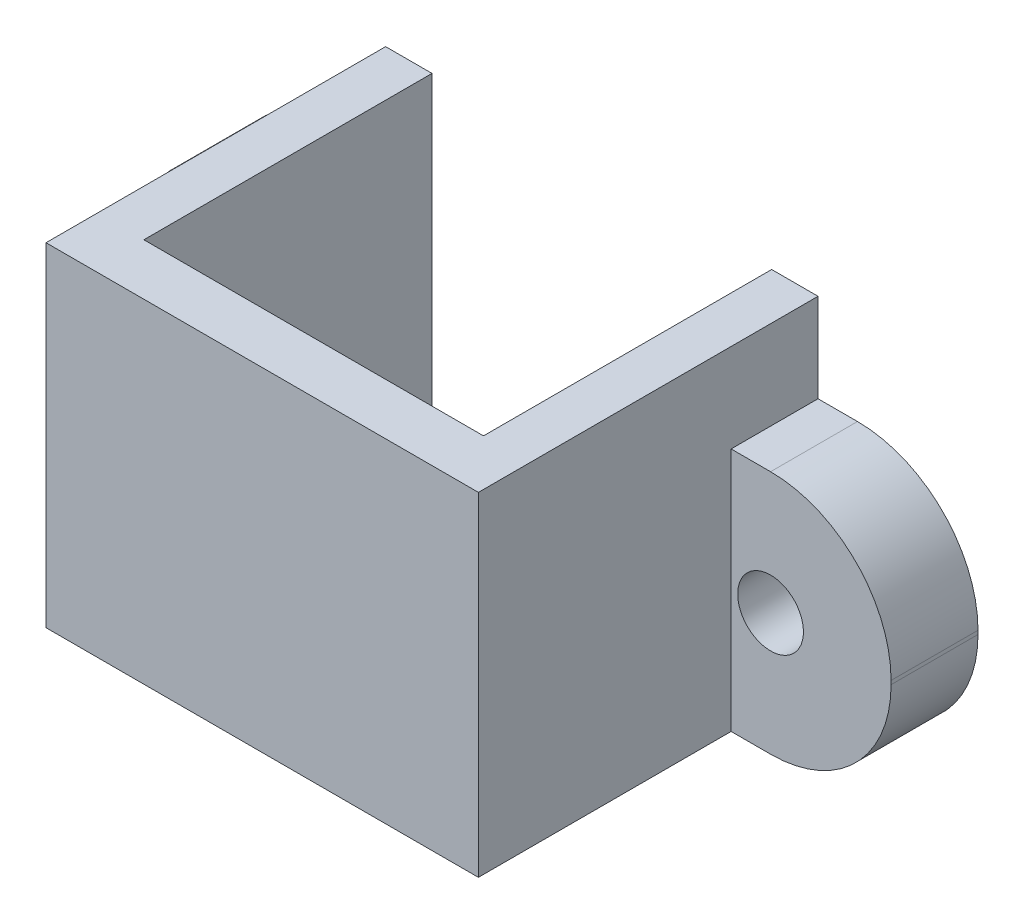
SolidWorks part; units mm, degrees
ref_plane "Front Plane" through (0, 0, 0) normal (0, 0, 1) x (1, 0, 0)
ref_plane "Top Plane" through (0, 0, 0) normal (0, 1, 0) x (1, 0, 0)
ref_plane "Right Plane" through (0, 0, 0) normal (1, 0, 0) x (0, 0, -1)
sketch "Sketch1" plane through (0, 0, 0) normal (0, 1, 0) x (1, 0, 0)
  line L0 (0, 0) -> (7.1755, 0)
  line L1 (7.1755, 0) -> (7.1755, -10.0203)
  line L2 (7.1755, -10.0203) -> (18.9865, -10.0203)
  line L3 (18.9865, -10.0203) -> (18.9865, 0)
  line L4 (18.9865, 0) -> (26.162, 0)
  line L5 (26.162, 0) -> (26.162, -3.0226)
  line L6 (0, -3.0226) -> (5.5626, -3.0226)
  line L7 (5.5626, -3.0226) -> (5.5626, -11.811)
  line L8 (5.5626, -11.811) -> (20.5994, -11.811)
  line L9 (20.5994, -11.811) -> (20.5994, -3.0226)
  line L10 (26.162, -3.0226) -> (20.5994, -3.0226)
  line L13 (0, 0) -> (0, -3.0226)
  dimension "D1" = 1.7907
  dimension "D2" = 1.6129
  dimension "D3" = 1.6129
  dimension "D4" = 3.0226
  dimension "D5" = 11.811
  dimension "D6" = 26.162
  dimension "0.465" = 11.811
extrude "Boss-Extrude1" add sketch "Sketch1" along normal blind 11.5951
sketch "Sketch2" plane through (0, 0, 11.811) normal (0, 0, 1) x (1, 0, 0)
  line L0 (5.5626, 11.5951) -> (0, 11.5951)
  line L1 (20.5994, 11.5951) -> (20.5994, 8.509)
  line L2 (20.5994, 11.5951) -> (20.5994, 0) construction
  line L3 (20.5994, 8.509) -> (21.971, 8.509)
  line L4 (26.162, 11.5951) -> (26.162, 0) construction
  line L5 (26.162, 4.318) -> (26.162, 4.191)
  line L6 (0, 11.5951) -> (0, 0)
  line L7 (0, 4.191) -> (0, 4.318)
  line L8 (0, 11.5951) -> (0, 0) construction
  line L9 (4.191, 8.509) -> (5.5626, 8.509)
  line L10 (5.5626, 11.5951) -> (5.5626, 0) construction
  line L11 (5.5626, 8.509) -> (5.5626, 11.5951)
  line L12 (0, 0) -> (4.191, 0)
  line L13 (20.5994, 11.5951) -> (26.162, 11.5951)
  line L14 (26.162, 11.5951) -> (26.162, 0)
  line L15 (26.162, 0) -> (21.971, 0)
  arc A0 (26.162, 4.191) -> (21.971, 0) centre (21.971, 4.191) cw
  arc A1 (0, 4.318) -> (4.191, 8.509) centre (4.191, 4.318) cw
  arc A2 (21.971, 8.509) -> (26.162, 4.318) centre (21.971, 4.318) cw
  arc A3 (4.191, 0) -> (0, 4.191) centre (4.191, 4.191) cw
  point P22 (26.162, 0)
  point P25 (0, 8.509)
  point P28 (26.162, 8.509)
  point P31 (0, 0)
  line M2 (20.5994, 0) -> (20.5994, 11.5951)
  line M4 (5.5626, 11.5951) -> (5.5626, 0)
  dimension "D2" = 4.191
  dimension "D3" = 4.191
  dimension "D4" = 4.191
  dimension "D1" = 8.509
extrude "Cut-Extrude4" cut sketch "Sketch2" against normal through all contours L6 A1 L9 L0 M4 | L12 A3 L6 | L3 A2 L14 L13 M2 | L14 A0 L15
sketch "Sketch4" plane through (0, 0, 3.0226) normal (0, 0, 1) x (1, 0, 0)
  line L0 (21.971, 8.509) -> (21.971, 0) construction
  line L1 (4.191, 8.509) -> (4.191, 0) construction
  circle A0 centre (4.191, 4.2545) radius 1.143
  circle A1 centre (21.971, 4.2545) radius 1.143
  dimension "D1" = 2.286
  dimension "D2" = 2.286
extrude "Cut-Extrude5" cut sketch "Sketch4" against normal through all
